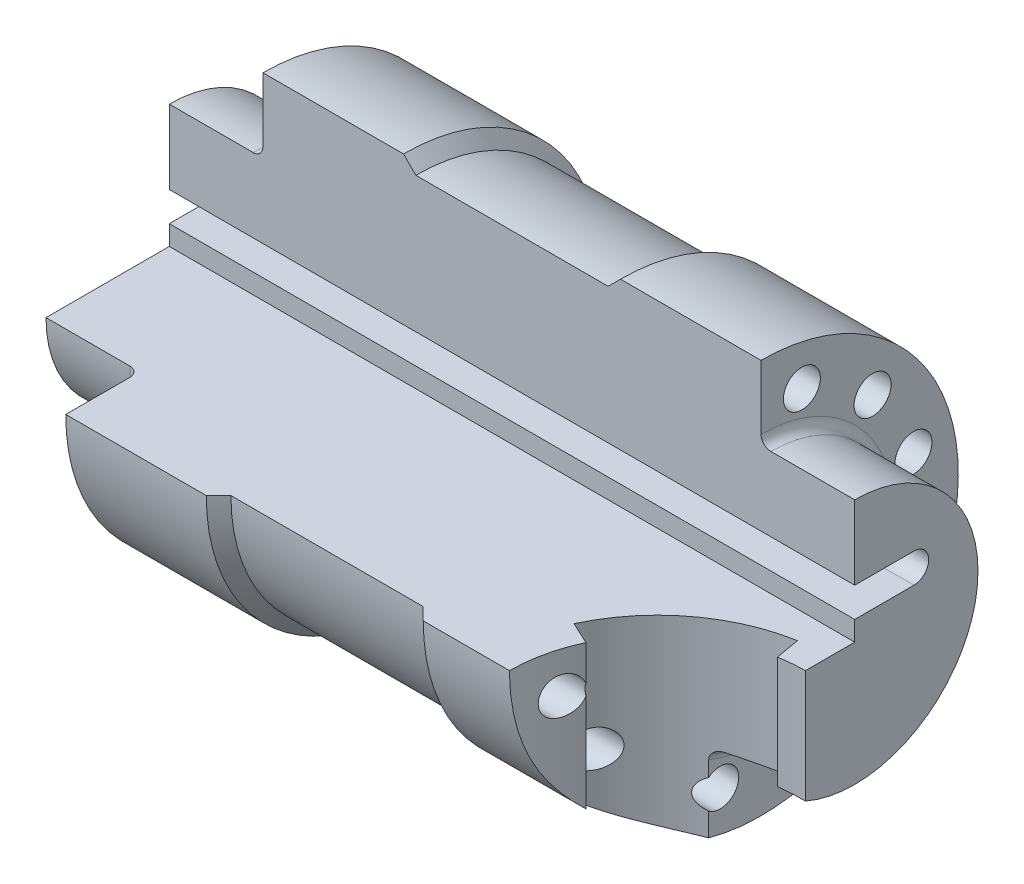
SolidWorks part; units mm, degrees
material "AISI 1020"
ref_plane "Front Plane" through (0, 0, 0) normal (0, 0, 1) x (1, 0, 0)
ref_plane "Top Plane" through (0, 0, 0) normal (0, 1, 0) x (1, 0, 0)
ref_plane "Right Plane" through (0, 0, 0) normal (1, 0, 0) x (0, 0, -1)
sketch "Sketch1" plane through (0, 0, 0) normal (0, 0, 1) x (1, 0, 0)
  line L13 (0, 0) -> (139, 0)
  line L14 (139, 0) -> (139, 25)
  line L15 (139, 25) -> (122, 25)
  line L16 (120, 27) -> (120, 40)
  line L17 (120, 40) -> (91.5, 40)
  line L18 (91.5, 40) -> (89, 37.5)
  line L19 (89, 37.5) -> (50, 37.5)
  line L20 (50, 37.5) -> (47.5, 40)
  line L21 (47.5, 40) -> (19, 40)
  line L22 (19, 40) -> (19, 27)
  line L23 (17, 25) -> (0, 25)
  line L24 (0, 25) -> (0, 0)
  arc A2 (122, 25) -> (120, 27) centre (122, 27) cw
  arc A3 (19, 27) -> (17, 25) centre (17, 27) cw
  point P15 (120, 25)
  point P18 (19, 25)
  dimension "D12" = 2
  dimension "D1" = 139
  dimension "D2" = 25
  dimension "D3" = 25
  dimension "D4" = 40
  dimension "D5" = 40
  dimension "D6" = 45
  dimension "D7" = 2.5
  dimension "D8" = 19
  dimension "D9" = 19
  dimension "D10" = 28.5
  dimension "D11" = 28.5
revolve "Revolve1" add sketch "Sketch1" angle 360 about L13
sketch "Sketch2" plane through (0, 0, 0) normal (-1, 0, 0) x (0, 0, 1)
  line L1 (0, 0) -> (44.8878, 0)
  line L2 (0, 0) -> (0, 40.8204)
  line L3 (0, 40.8204) -> (44.8878, 40.8204)
  line L4 (44.8878, 0) -> (44.8878, 40.8204)
extrude "Cut-Extrude1" cut sketch "Sketch2" against normal through all
sketch "Sketch4" plane through (0, 0, 0) normal (-1, 0, 0) x (0, 0, 1)
  line L0 (0, 7) -> (-12, 7) construction
  line L1 (0, 25) -> (0, 0) construction
  line L2 (0, 4) -> (-12, 4)
  line L3 (0, 10) -> (-12, 10)
  line L4 (0, 0) -> (25, 0) construction
  arc A0 (0, 4) -> (0, 10) centre (0, 7) ccw
  arc A1 (-12, 10) -> (-12, 4) centre (-12, 7) ccw
  point P4 (-6, 7)
  dimension "D1" = 3
  dimension "D2" = 12
  dimension "D3" = 7
extrude "Cut-Extrude2" cut sketch "Sketch4" against normal through all
sketch "Sketch5" plane through (19, 0, 0) normal (-1, 0, 0) x (0, 0, 1)
  line L0 (0, 27) -> (0, 40) construction
  line L1 (0, 0) -> (-8.2822, 30.9096) construction
  line L2 (0, 0) -> (30.9096, -8.2822) construction
  line L3 (40, 0) -> (27, 0) construction
  circle A0 centre (0, 0) radius 32 construction
  circle A1 centre (-8.2822, 30.9096) radius 3.75
  circle A2 centre (-22.623, 22.6266) radius 3.75
  circle A3 centre (-30.9017, 8.2834) radius 3.75
  circle A4 centre (-30.9004, -8.2776) radius 3.75
  circle A5 centre (-22.6196, -22.6196) radius 3.75
  circle A6 centre (-8.2776, -30.9004) radius 3.75
  circle A7 centre (8.2834, -30.9017) radius 3.75
  circle A8 centre (22.6266, -22.623) radius 3.75
  circle A9 centre (30.9096, -8.2822) radius 3.75
  point P25 (0.0052, 0.0052)
  point P26 (0, 0)
  dimension "D1" = 64
  dimension "D2" = 7.5
  dimension "D3" = 15
  dimension "D5" = 15
  dimension "D4" = 9
extrude "Cut-Extrude3" cut sketch "Sketch5" against normal through all
sketch "Sketch6" plane through (0, 0, 0) normal (0, 1, 0) x (1, 0, 0)
  line L0 (139, -25) -> (139, -44.6739) construction
  line L1 (120, -40) -> (139, -40) construction
  line L2 (107.2792, -25.2084) -> (111.8108, -27.3215)
  line L3 (132.9223, -5.5317) -> (133.7906, -10.4558)
  line L4 (120, -40) -> (91.5, -40) construction
  line L5 (139, 0) -> (139, -25) construction
  arc A0 (111.8108, -27.3215) -> (133.7906, -10.4558) centre (139, -40) ccw
  arc A1 (107.2792, -25.2084) -> (132.9223, -5.5317) centre (139, -40) cw
  dimension "D1" = 60
  dimension "D2" = 35
  dimension "D3" = 25
  dimension "D4" = 10
extrude "Cut-Extrude4" cut sketch "Sketch6" against normal through all
sketch "Sketch7" plane through (0, 0, 0) normal (-1, 0, 0) x (0, 0, 1)
  line L4 (-4, 0) -> (-21, 0)
  line L14 (-12, 4) -> (0, 4) construction
  line L15 (-4, -4) -> (-4, 4)
  line L16 (20.6155, -4) -> (-4, -4)
  line L17 (-4, -4) -> (-4, 0)
  line L18 (20.6155, -4) -> (-4, -4)
  arc A7 (0, 21) -> (20.6155, -4) centre (0, 0) ccw
  arc A8 (-21, 0) -> (20.6155, -4) centre (0, 0) ccw
  dimension "D2" = 4
  dimension "D1" = 4
extrude "Cut-Extrude5" cut sketch "Sketch7" against normal blind 10
fillet "Fillet1" radius 1 8 edges at (0, -2, -4) (0, -4, 8.3078) (0, 0, -12.5) (0, -20.9037, -2.0092) (10, -2, -4) (10, -4, 8.3078) (10, -20.9037, -2.0092) (10, 0, -12.5)
equation "\"a\" = 139mm"
equation "\"b\"= 19mm"
equation "\"c\"= 28.5mm"
